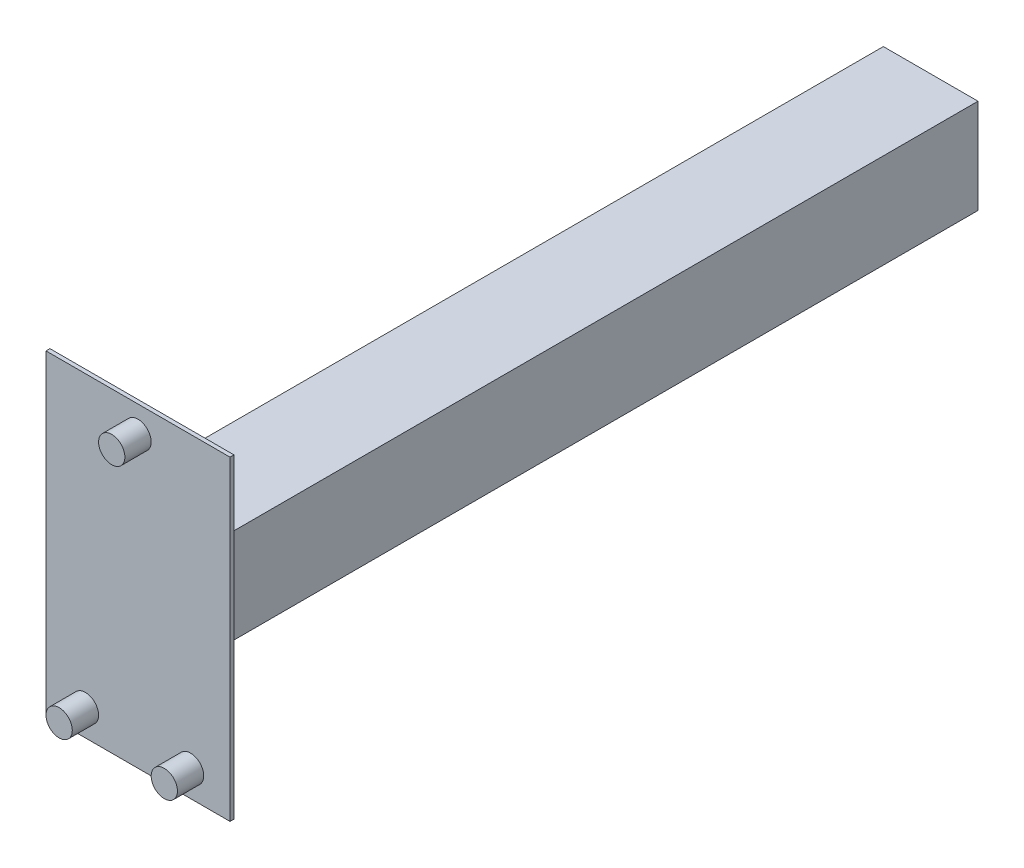
SolidWorks part; units mm, degrees
ref_plane "Front Plane" through (0, 0, 0) normal (0, 0, 1) x (1, 0, 0)
ref_plane "Top Plane" through (0, 0, 0) normal (0, 1, 0) x (1, 0, 0)
ref_plane "Right Plane" through (0, 0, 0) normal (1, 0, 0) x (0, 0, -1)
sketch "Sketch1" plane through (0, 0, 0) normal (0, 0, 1) x (1, 0, 0)
  line L1 (-18, -18) -> (18, -18)
  line L2 (-18, -18) -> (-18, 18)
  line L3 (-18, 18) -> (18, 18)
  line L4 (18, -18) -> (18, 18)
  line L5 (-18, -18) -> (18, 18) construction
  line L6 (-18, 18) -> (18, -18) construction
  point P0 (0, 0)
  dimension "D1" = 36
extrude "Boss-Extrude1" add sketch "Sketch1" along normal blind 300
sketch "Sketch2" plane through (0, 0, 300) normal (0, 0, 1) x (1, 0, 0)
  line L1 (-35, 60) -> (35, 60)
  line L2 (-35, 60) -> (-35, -60)
  line L3 (-35, -60) -> (35, -60)
  line L4 (35, 60) -> (35, -60)
  point P4 (0, -60)
  point P6 (35, 0)
  dimension "D1" = 70
  dimension "D2" = 120
extrude "Boss-Extrude2" add sketch "Sketch2" along normal blind 1.5
sketch "Sketch3" plane through (0, 0, 301.5) normal (0, 0, 1) x (1, 0, 0)
  line L0 (35, 60) -> (-35, 60) construction
  line L1 (-35, -60) -> (35, -60) construction
  line L2 (35, -60) -> (35, 60) construction
  circle A0 centre (0, 50) radius 5
  circle A1 centre (-20, -50) radius 5
  circle A2 centre (20, -50) radius 5
  point P6 (0, 0)
  point P7 (0, 0)
  dimension "D5" = 10
  dimension "D1" = 20
  dimension "D2" = 20
  dimension "D3" = 10
  dimension "D4" = 10
  dimension "D6" = 35
extrude "Boss-Extrude3" add sketch "Sketch3" along normal blind 10
equation "\"D2@Sketch3\"=\"D1@Sketch3\""
